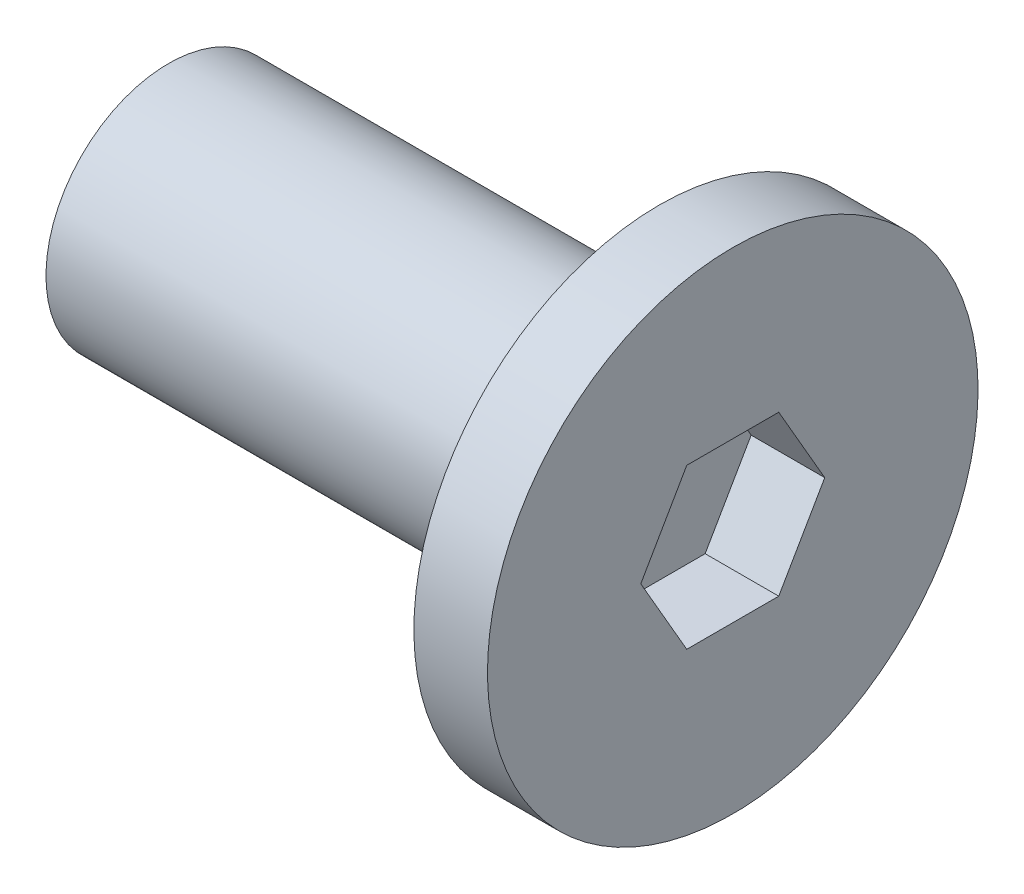
SolidWorks part; units mm, degrees
material "AISI 304"
ref_plane "前视基准面" through (0, 0, 0) normal (0, 0, 1) x (1, 0, 0)
ref_plane "上视基准面" through (0, 0, 0) normal (0, 1, 0) x (1, 0, 0)
ref_plane "右视基准面" through (0, 0, 0) normal (1, 0, 0) x (0, 0, -1)
sketch "草图1" plane through (0, 0, 0) normal (0, 0, 1) x (1, 0, 0)
  line L0 (0, 0) -> (-1.2, 0)
  line L1 (-1.2, 0) -> (-1.2, 4)
  line L2 (-1.2, 4) -> (0, 4)
  line L3 (0, 4) -> (0, 0)
  dimension "D1" = 4
  dimension "D2" = 1.2
revolve "旋转1" add sketch "草图1" angle 360 about L0
sketch "草图2" plane through (-1.2, 0, 0) normal (-1, 0, 0) x (0, 0, 1)
  circle A0 centre (0, 0) radius 2
  dimension "D1" = 4
extrude "凸台-拉伸1" add sketch "草图2" along normal blind 8
cosmetic thread "装饰螺纹线1" parameters "D2"=3.242
sketch "草图3" plane through (0, 0, 0) normal (1, 0, 0) x (0, 0, -1)
  line L1 (0.75, 1.299) -> (-0.75, 1.299)
  line L2 (-0.75, 1.299) -> (-1.5, 0)
  line L3 (-1.5, 0) -> (-0.75, -1.299)
  line L4 (-0.75, -1.299) -> (0.75, -1.299)
  line L5 (0.75, -1.299) -> (1.5, 0)
  line L6 (1.5, 0) -> (0.75, 1.299)
  circle A0 centre (0, 0) radius 1.299 construction
  dimension "D1" = 3
extrude "切除-拉伸1" cut sketch "草图3" against normal blind 1.2
